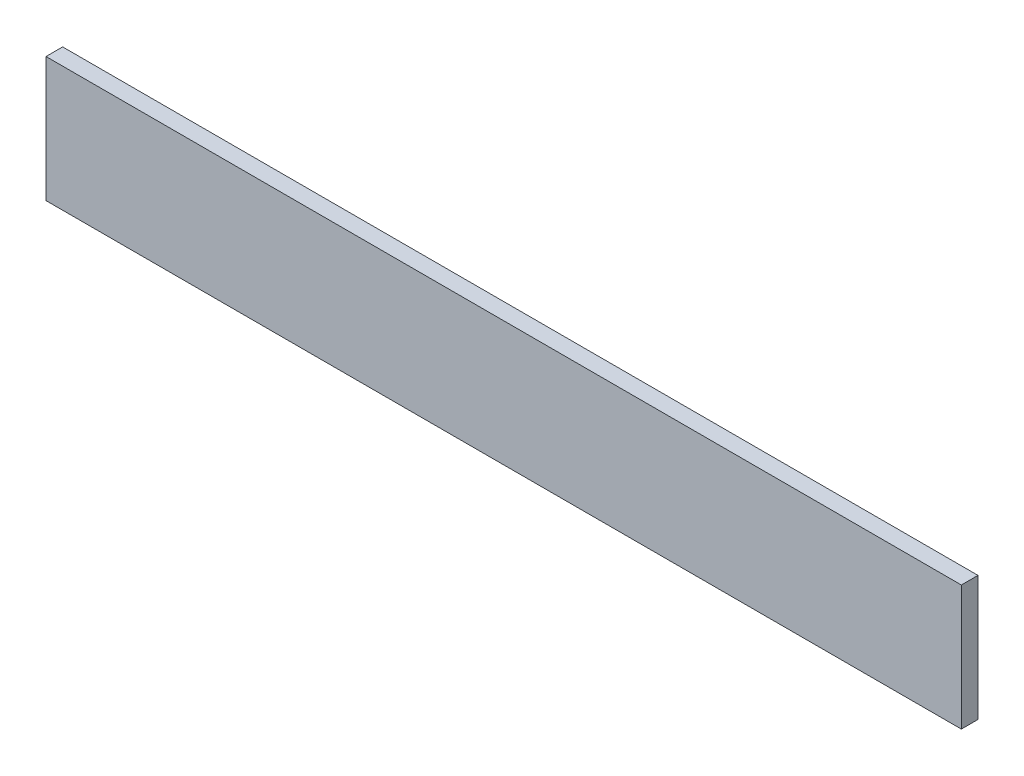
SolidWorks part; units mm, degrees
ref_plane "Alzado" through (0, 0, 0) normal (0, 0, 1) x (1, 0, 0)
ref_plane "Planta" through (0, 0, 0) normal (0, 1, 0) x (1, 0, 0)
ref_plane "Vista lateral" through (0, 0, 0) normal (1, 0, 0) x (0, 0, -1)
sketch "Croquis1" plane through (0, 0, 0) normal (0, 0, 1) x (1, 0, 0)
  line L1 (0, 0) -> (220, 0)
  line L2 (0, 0) -> (0, -30)
  line L3 (0, -30) -> (220, -30)
  line L4 (220, 0) -> (220, -30)
  dimension "D1" = 30
  dimension "D2" = 220
extrude "Saliente-Extruir1" add sketch "Croquis1" along normal blind 4
